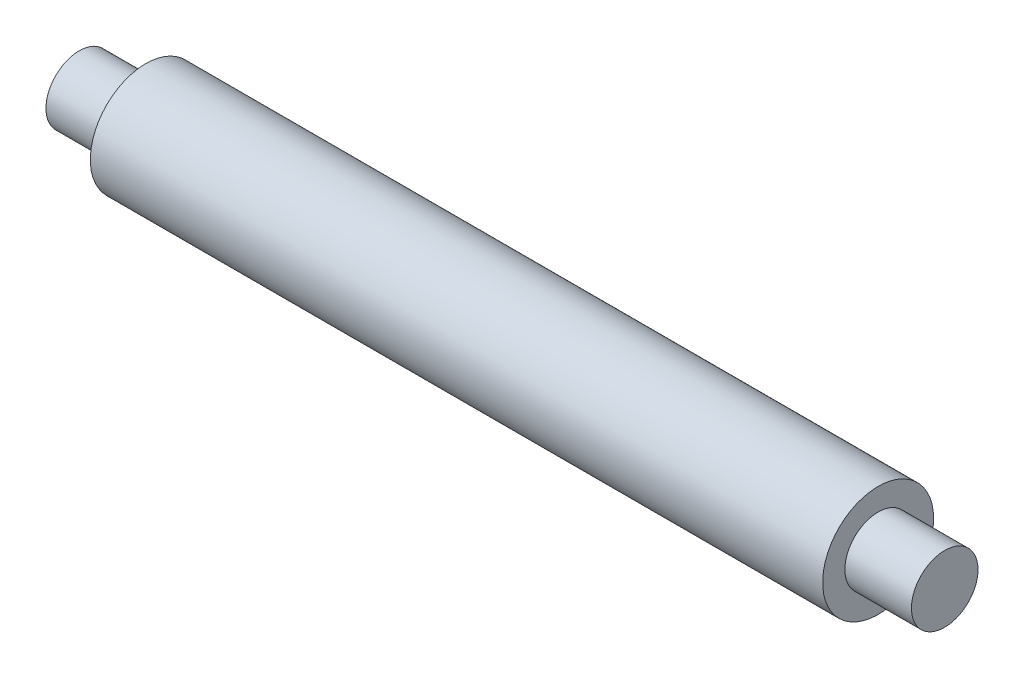
SolidWorks part; units mm, degrees
ref_plane "Front Plane" through (0, 0, 0) normal (0, 0, 1) x (1, 0, 0)
ref_plane "Top Plane" through (0, 0, 0) normal (0, 1, 0) x (1, 0, 0)
ref_plane "Right Plane" through (0, 0, 0) normal (1, 0, 0) x (0, 0, -1)
sketch "Sketch1" plane through (0, 0, 0) normal (0, 0, 1) x (1, 0, 0)
  line L0 (19.5, 0) -> (-19.5, 0) construction
  line L1 (-19.5, 0) -> (-19.5, 1.5)
  line L2 (-19.5, 1.5) -> (-16.5, 1.5)
  line L3 (-16.5, 1.5) -> (-16.5, 2.5)
  line L4 (-16.5, 2.5) -> (16.5, 2.5)
  line L5 (16.5, 2.5) -> (16.5, 1.5)
  line L6 (16.5, 1.5) -> (19.5, 1.5)
  line L7 (19.5, 1.5) -> (19.5, 0)
  line L8 (-19.5, 0) -> (19.5, 0)
  point P0 (0, 2.5)
  point P4 (0, 0)
  dimension "D1" = 33
  dimension "D2" = 3
  dimension "D3" = 3
  dimension "D4" = 5
revolve "Revolve1" add sketch "Sketch1" angle 360 about L0
